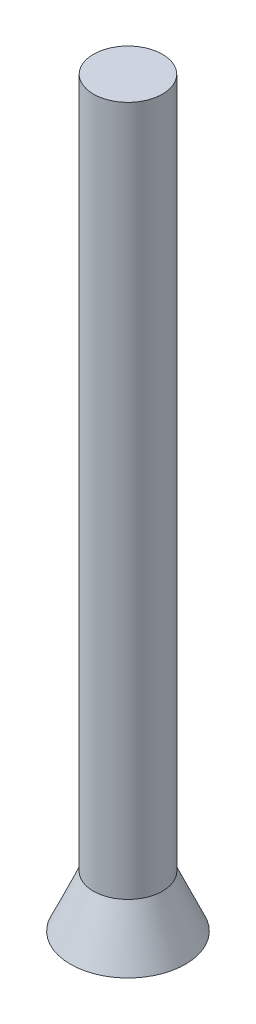
SolidWorks part; units mm, degrees
ref_plane "Front Plane" through (0, 0, 0) normal (0, 0, 1) x (1, 0, 0)
ref_plane "Top Plane" through (0, 0, 0) normal (0, 1, 0) x (1, 0, 0)
ref_plane "Right Plane" through (0, 0, 0) normal (1, 0, 0) x (0, 0, -1)
sketch "Sketch1" plane through (0, 0, 0) normal (0, 1, 0) x (1, 0, 0)
  circle A0 centre (0, 0) radius 2.5
extrude "Boss-Extrude1" add sketch "Sketch1" along normal blind 2.25 draft 24
sketch "Sketch2" plane through (0, 2.25, 0) normal (0, 1, 0) x (1, 0, 0)
  circle A0 centre (0, 0) radius 1.5
extrude "Boss-Extrude2" add sketch "Sketch2" along normal blind 30
cosmetic thread "Cosmetic Thread5" parameters "D2"=2.439
sketch "Sketch3" plane through (0, 0, 0) normal (0, -1, 0) x (-1, 0, 0)
  line L0 (0, 0) -> (0, -1.6875) construction
  line L1 (0, 0) -> (-3.4963, 0) construction
  line L2 (-0.5, 0.5) -> (-0.5, 2)
  line L3 (0.5, -2) -> (-0.5, -2)
  line L4 (0.5, -2) -> (0.5, -0.5)
  line L5 (0.5, 2) -> (-0.5, 2)
  line L6 (-0.5, -2) -> (-0.5, -0.5)
  line L7 (0.5, -2) -> (-0.5, 2) construction
  line L8 (0.5, 2) -> (-0.5, -2) construction
  line L9 (2, -0.5) -> (0.5, -0.5)
  line L10 (2, -0.5) -> (2, 0.5)
  line L11 (2, 0.5) -> (0.5, 0.5)
  line L12 (-2, -0.5) -> (-2, 0.5)
  line L13 (2, -0.5) -> (-2, 0.5) construction
  line L14 (2, 0.5) -> (-2, -0.5) construction
  line L15 (0.5, 0.5) -> (0.5, 2)
  line L16 (-0.5, -0.5) -> (-2, -0.5)
  line L17 (-0.5, 0.5) -> (-2, 0.5)
  point P4 (0, 0)
  point P12 (0, 0)
extrude "Cut-Extrude1" cut sketch "Sketch3" against normal blind 1.5 draft 16.5
